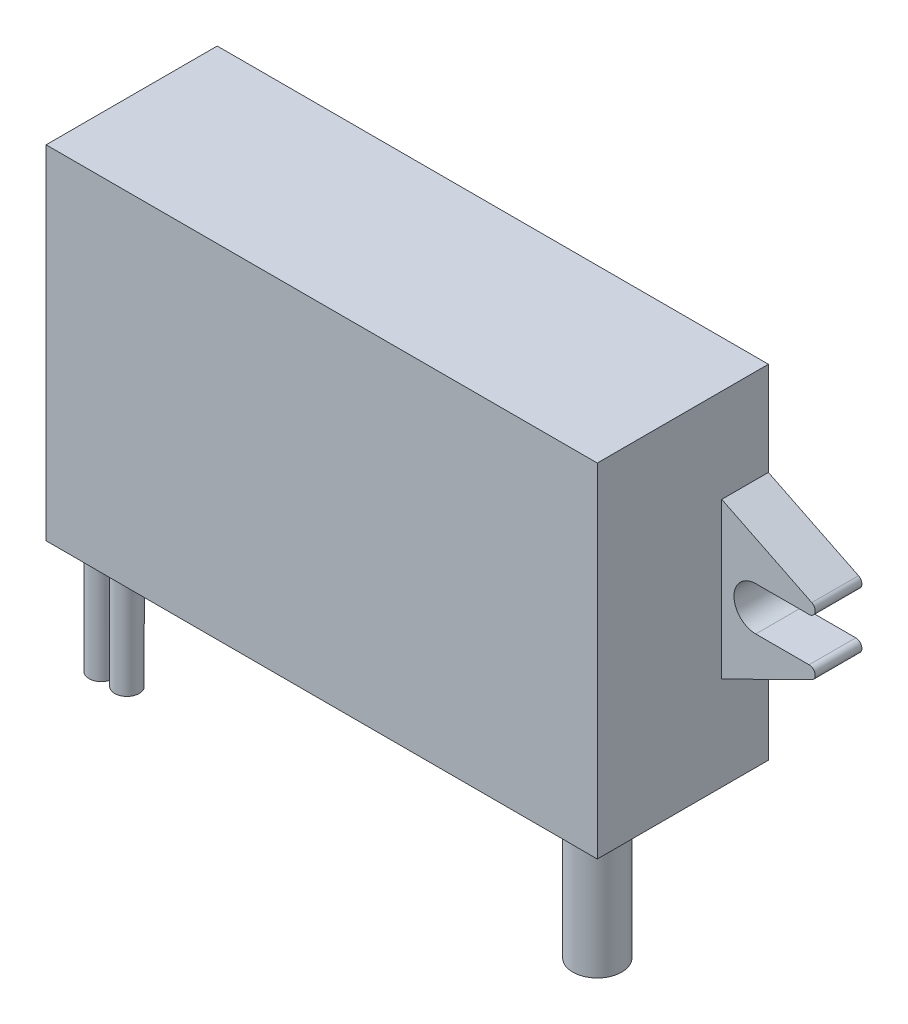
SolidWorks part; units mm, degrees
ref_plane "Front Plane" through (0, 0, 0) normal (0, 0, 1) x (1, 0, 0)
ref_plane "Top Plane" through (0, 0, 0) normal (0, 1, 0) x (1, 0, 0)
ref_plane "Right Plane" through (0, 0, 0) normal (1, 0, 0) x (0, 0, -1)
sketch "Sketch1" plane through (0, 0, 0) normal (0, 0, 1) x (1, 0, 0)
  line L1 (-22.5, 14) -> (22.5, 14)
  line L2 (-22.5, 14) -> (-22.5, -14)
  line L3 (-22.5, -14) -> (22.5, -14)
  line L4 (22.5, 14) -> (22.5, -14)
  line L5 (-22.5, 14) -> (22.5, -14) construction
  line L6 (-22.5, -14) -> (22.5, 14) construction
  point P0 (0, 0)
  dimension "D1" = 28
  dimension "D2" = 45
extrude "Boss-Extrude1" add sketch "Sketch1" along normal blind 13.97
sketch "Sketch3" plane through (0, 0, 0) normal (0, 0, -1) x (-1, 0, 0)
  line L0 (-22.5, 0) -> (-23.5, 0) construction
  line L1 (-22.5, -14) -> (-22.5, 14) construction
  line L2 (-22.5, 6.35) -> (-29.854, 2.7265)
  line L3 (-29.633, 1.778) -> (-25.278, 1.778)
  line L5 (-25.278, -1.778) -> (-29.633, -1.778)
  line L6 (-29.854, -2.7265) -> (-22.5, -6.35)
  line L7 (-22.5, -6.35) -> (-22.5, 6.35)
  line L9 (-23.5, 0) -> (-31.7791, 0) construction
  line L10 (-31.7791, 0) -> (-31.7791, 1.778) construction
  line L11 (-31.7791, 0) -> (-31.7791, -1.778) construction
  arc A0 (-25.278, 1.778) -> (-25.278, -1.778) centre (-25.278, 0) cw
  arc A1 (-29.633, -1.778) -> (-29.854, -2.7265) centre (-29.633, -2.278) ccw
  arc A2 (-29.854, 2.7265) -> (-29.633, 1.778) centre (-29.633, 2.278) ccw
  point P12 (-24.8447, 0)
  point P20 (-32.4234, 1.778)
  point P21 (-30.12, 2.1645)
  dimension "D4" = 0.5
  dimension "D1" = 3.556
  dimension "D2" = 12.7
  dimension "D3" = 1
  dimension "D5" = 7.62
extrude "Boss-Extrude2" add sketch "Sketch3" against normal blind 3.81
mirror "Mirror8" about plane through (0, 0, 0) normal (1, 0, 0) of "Boss-Extrude2"
sketch "Sketch4" plane through (0, -14, 0) normal (0, -1, 0) x (1, 0, 0)
  line L0 (-22.5, 10.97) -> (22.5, 10.97) construction
  line L1 (-22.5, 13.97) -> (-22.5, 0) construction
  line L2 (22.5, 13.97) -> (22.5, 0) construction
  line L3 (-22.5, 13.97) -> (22.5, 13.97) construction
  circle A0 centre (-21, 10.97) radius 1
  circle A1 centre (-18.9, 10.97) radius 1
  circle A2 centre (19.5, 10.97) radius 2
  point P14 (-19.7432, 10.97)
  point P15 (-16.7763, 10.97)
  dimension "D4" = 2
  dimension "D6" = 4
  dimension "D1" = 3
  dimension "D2" = 1.5
  dimension "D3" = 2.1
  dimension "D5" = 3
extrude "Boss-Extrude3" add sketch "Sketch4" along normal blind 10
